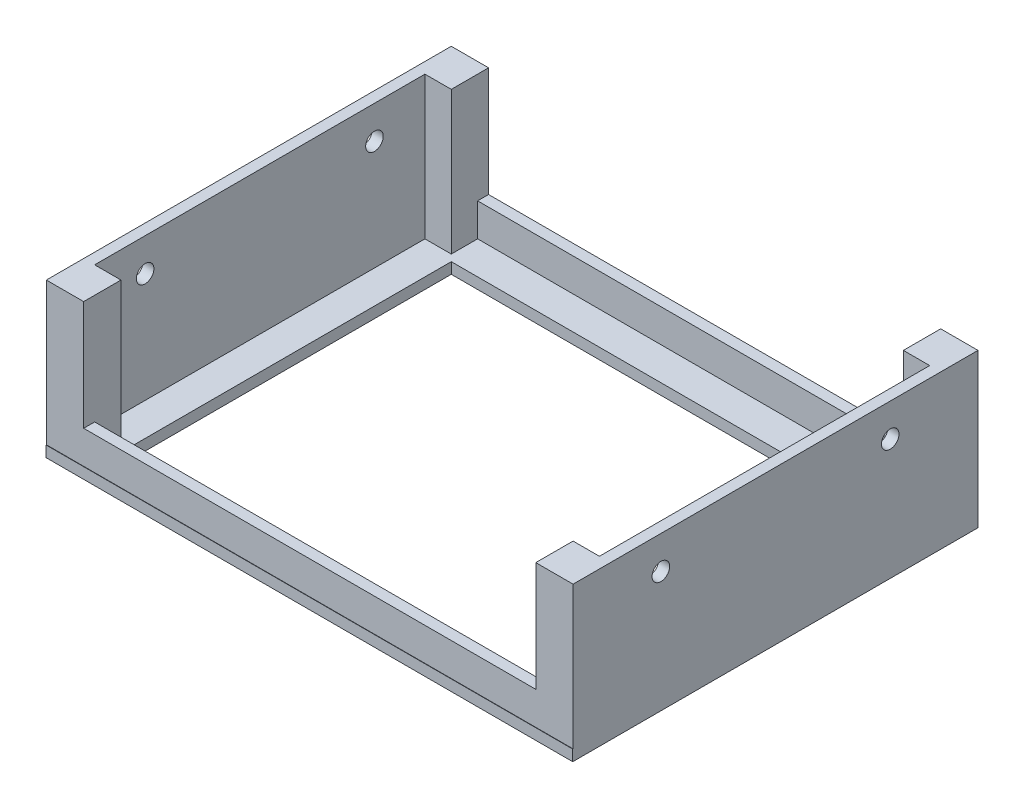
SolidWorks part; units mm, degrees
ref_plane "Ebene vorne" through (0, 0, 0) normal (0, 0, 1) x (1, 0, 0)
ref_plane "Ebene oben" through (0, 0, 0) normal (0, 1, 0) x (1, 0, 0)
ref_plane "Ebene rechts" through (0, 0, 0) normal (1, 0, 0) x (0, 0, -1)
sketch "Skizze1" plane through (0, 0, 0) normal (0, 1, 0) x (1, 0, 0)
  line L0 (0, 0) -> (0, 56.5954)
  line L1 (120, -92.25) -> (-120, -92.25)
  line L2 (120, -92.25) -> (120, 92.25)
  line L3 (120, 92.25) -> (-120, 92.25)
  line L4 (-120, -92.25) -> (-120, 92.25)
  line L5 (120, -92.25) -> (112.4684, -86.4601) construction
  line L7 (103, 87.25) -> (-103, 87.25)
  line L8 (115, -75.25) -> (115, 75.25)
  line L10 (-115, -75.25) -> (-115, 75.25)
  line L11 (103, -78.1457) -> (-103, 78.1457) construction
  line L12 (103, 78.1457) -> (-103, -78.1457) construction
  line L13 (-115, -75.25) -> (-103, -75.25)
  line L14 (103, -87.25) -> (-103, -87.25)
  line L15 (103, -79.1813) -> (-103, 79.1813) construction
  line L16 (-103, -75.25) -> (-103, -87.25)
  line L17 (103, -75.25) -> (103, -87.25)
  line L18 (115, -75.25) -> (103, -75.25)
  line L19 (0, 0) -> (44.0429, 0)
  line L20 (-103, 75.25) -> (-103, 87.25)
  line L21 (103, 75.25) -> (103, 87.25)
  line L22 (115, 75.25) -> (103, 75.25)
  line L23 (-115, 75.25) -> (-103, 75.25)
  line L24 (103, 79.1813) -> (-103, -79.1813) construction
  point P0 (0, 0)
  point P5 (0, 0)
  dimension "D1" = 184.5
  dimension "D2" = 240
  dimension "D3" = 5
  dimension "D4" = 5
  dimension "D5" = 12
  dimension "D6" = 12
  dimension "D7" = 5
  dimension "D8" = 5
  dimension "D9" = 44.0429
  dimension "D10" = 56.5954
extrude "Aufsatz-Linear austragen1" add sketch "Skizze1" along normal blind 70 contours L10 L23 L20 L7 L21 L22 L8 L18 L17 L14 L16 L13 | L1 L4 L3 L2
sketch "Skizze2" plane through (0, 0, 92.25) normal (0, 0, 1) x (1, 0, 0)
  line L0 (120, 70) -> (-120, 70) construction
  line L1 (-103, 70) -> (103, 70)
  line L2 (-103, 70) -> (-103, 20)
  line L3 (-103, 20) -> (103, 20)
  line L4 (103, 70) -> (103, 20)
  line L5 (120, 0) -> (-120, 0) construction
  line L6 (-103, 70) -> (-103, 0) construction
  line L7 (103, 70) -> (103, 0) construction
  dimension "D1" = 20
extrude "Schnitt-Linear austragen3" cut sketch "Skizze2" against normal through all contours L2 L3 L4 L1
sketch "Skizze3" plane through (0, 0, 0) normal (0, 1, 0) x (1, 0, 0)
  line L0 (-120, 92.25) -> (120, 92.25)
  line L1 (-120, 92.25) -> (-120, -92.4122)
  line L2 (120, 92.25) -> (120, -92.4122)
  line L3 (-120, -92.4122) -> (120, -92.4122)
  line L5 (100, -72.25) -> (-100, -72.25)
  line L6 (100, -72.25) -> (100, 72.25)
  line L7 (100, 72.25) -> (-100, 72.25)
  line L8 (-100, -72.25) -> (-100, 72.25)
  line L9 (100, -72.25) -> (-100, 72.25) construction
  line L10 (100, 72.25) -> (-100, -72.25) construction
  point P0 (0, 0)
  dimension "D1" = 20
  dimension "D2" = 20
extrude "Aufsatz-Linear austragen2" add sketch "Skizze3" along normal blind 5 contours L5 L8 L7 L6 | L1 L3 L2 L0
sketch "Skizze6" plane through (0, 0, 0) normal (0, -1, 0) x (1, 0, 0)
  line L0 (115, -72.25) -> (100, -87.25)
  line L1 (100, -72.25) -> (115, -72.25)
  line L2 (100, -72.25) -> (100, -87.25)
  line L3 (100, -87.25) -> (115, -87.25)
  line L4 (115, -72.25) -> (115, -87.25)
  line L5 (100, -72.25) -> (115, -87.25)
  point P4 (107.5, -79.75)
  dimension "D1" = 15
  dimension "D2" = 15
hole_wizard "Kernloch für M4x0.71" positions "3D-Skizze1" profile "Skizze7" hole size "M4x0.7" standard "ANSI Metrisch"
sketch3d "3D-Skizze1"
  point P0 (107.5, 0, -79.75)
  point P3 (107.5, 0, -79.75)
sketch "Skizze7" plane through (107.5, 0, -79.75) normal (1, 0, 0) x (0, 0, -1)
  line L0 (0, 0) -> (0, 20.9914)
  line L1 (0, 20.9914) -> (1.65, 20)
  line L2 (1.65, 20) -> (1.65, 0)
  line L5 (1.65, 0) -> (0, 0)
  line L10 (0, 20.9914) -> (-1.65, 20) construction
  line L11 (0, -6.35) -> (0, 107.95) construction
  dimension "Bohrerdurchmesser" = 3.3
  dimension "Bohrungstiefe" = 20
  dimension "Spitzenwinkel" = 118
ref_plane "Ebene1" through (0, 0, 0) normal (-1, 0, 0) x (0, 0, 1)
ref_plane "Ebene2" through (0, 0, 0) normal (0, 0, -1) x (-1, 0, 0)
mirror "Spiegeln1" about plane through (0, 0, 0) normal (-1, 0, 0) of "Kernloch für M4x0.71"
mirror "Spiegeln2" about plane through (0, 0, 0) normal (0, 0, -1) of "Spiegeln1", "Kernloch für M4x0.71"
sketch "Skizze11" plane through (-120, 0, 0) normal (-1, 0, 0) x (0, 0, 1)
  line L1 (92.25, 70) -> (-92.25, 70) construction
  line L2 (-92.25, 70) -> (-92.25, 0) construction
  circle A0 centre (-52.25, 55) radius 11.6717
  point P8 (-14.595, 22.6978)
  dimension "D1" = 40
  dimension "D2" = 15
hole_wizard "Ø8.0mm Stiftloch1" positions "Skizze15" profile "Skizze16" hole size "Ø8.0" standard "ANSI Metrisch" end condition through all
sketch "Skizze15" plane through (-120, 0, 0) normal (-1, 0, 0) x (0, 0, 1)
  point P0 (-52.25, 55)
sketch "Skizze16" plane through (-120, 55, -52.25) normal (0, 1, 0) x (0, 0, 1)
  line L0 (0, 0) -> (0, 240)
  line L1 (0, 240) -> (4, 240)
  line L2 (4, 240) -> (4, 0)
  line L5 (4, 0) -> (0, 0)
  line L11 (0, -6.35) -> (0, 107.95) construction
  dimension "Bohrerdurchmesser" = 8
  dimension "Bohrungstiefe" = 240
mirror "Spiegeln3" about plane through (0, 0, 0) normal (0, 0, -1) of "Ø8.0mm Stiftloch1"
